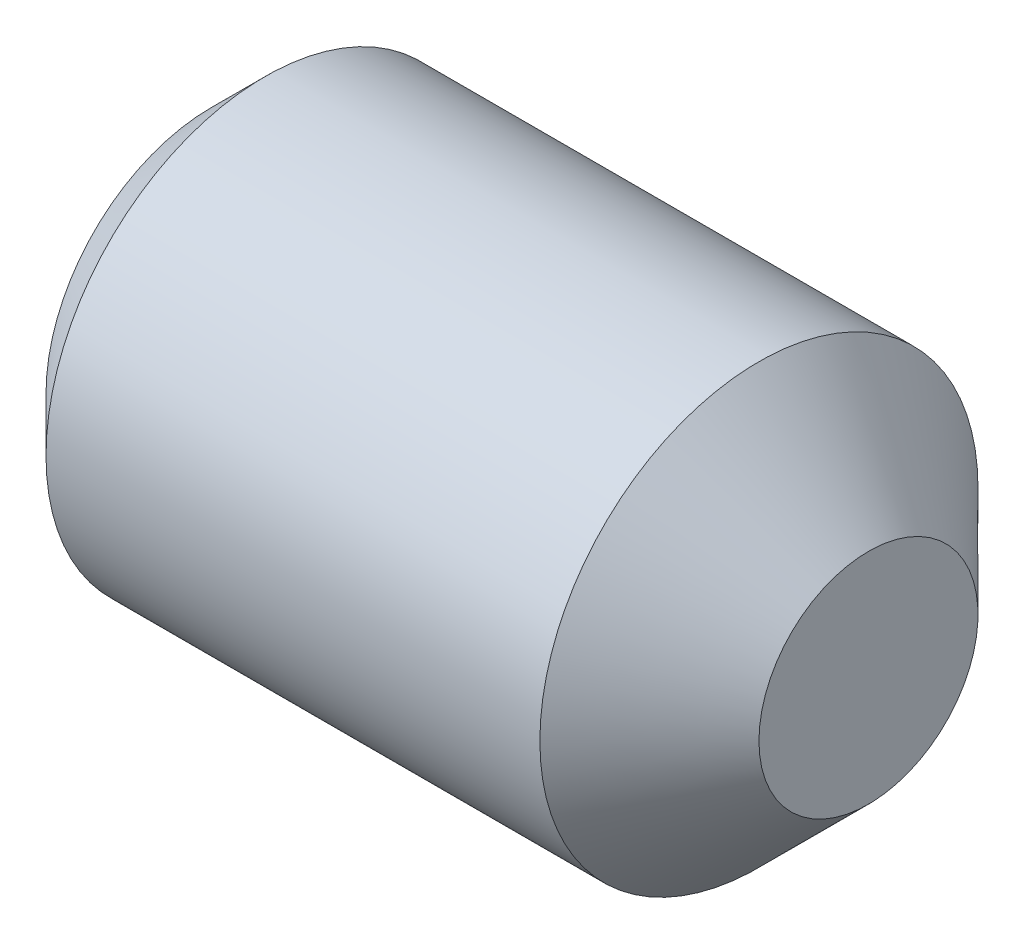
SolidWorks part; units mm, degrees
ref_plane "Front Plane" through (0, 0, 0) normal (0, 0, 1) x (1, 0, 0)
ref_plane "Top Plane" through (0, 0, 0) normal (0, 1, 0) x (1, 0, 0)
ref_plane "Right Plane" through (0, 0, 0) normal (1, 0, 0) x (0, 0, -1)
ref_plane "Plane1" through (0, 0, 0) normal (0, 0, 1) x (1, 0, 0)
sketch "Sketch1" plane through (0, 0, 0) normal (0, 0, 1) x (1, 0, 0)
  line L0 (-3, 0) -> (-3, 0.7545)
  line L1 (-3, 0.7545) -> (-2.7545, 1)
  line L2 (-2.7545, 1) -> (-0.5, 1)
  line L3 (-0.5, 1) -> (0, 0.5)
  line L4 (0, 0.5) -> (0, 0)
  line L5 (0, 0) -> (-3, 0)
  line L6 (0, 0) -> (-3, 0) construction
revolve "Revolve1" add sketch "Sketch1" angle 360 about L6
ref_plane "Plane2" through (-3, 0, 0) normal (-1, 0, 0) x (0, 0, 1)
sketch "Sketch2" plane through (-3, 0, 0) normal (-1, 0, 0) x (0, 0, 1)
  line L0 (-0.2598, -0.45) -> (0.2598, -0.45)
  line L1 (0.2598, -0.45) -> (0.5196, 0)
  line L2 (0.5196, 0) -> (0.2598, 0.45)
  line L3 (0.2598, 0.45) -> (-0.2598, 0.45)
  line L4 (-0.2598, 0.45) -> (-0.5196, 0)
  line L5 (-0.5196, 0) -> (-0.2598, -0.45)
extrude "Cut-Extrude1" cut sketch "Sketch2" against normal blind 0.8
ref_plane "Plane3" through (0, 0, 0) normal (0, 0, 1) x (1, 0, 0)
sketch "Sketch3" plane through (0, 0, 0) normal (0, 0, 1) x (1, 0, 0)
  line L0 (-2.2, 0) -> (-2.2, 0.45)
  line L1 (-2.2, 0.45) -> (-1.9402, 0)
  line L2 (-1.9402, 0) -> (-2.2, 0)
  line L3 (-1.9402, 0) -> (-2.2, 0) construction
revolve "Cut-Revolve1" cut sketch "Sketch3" angle 360 about L3
